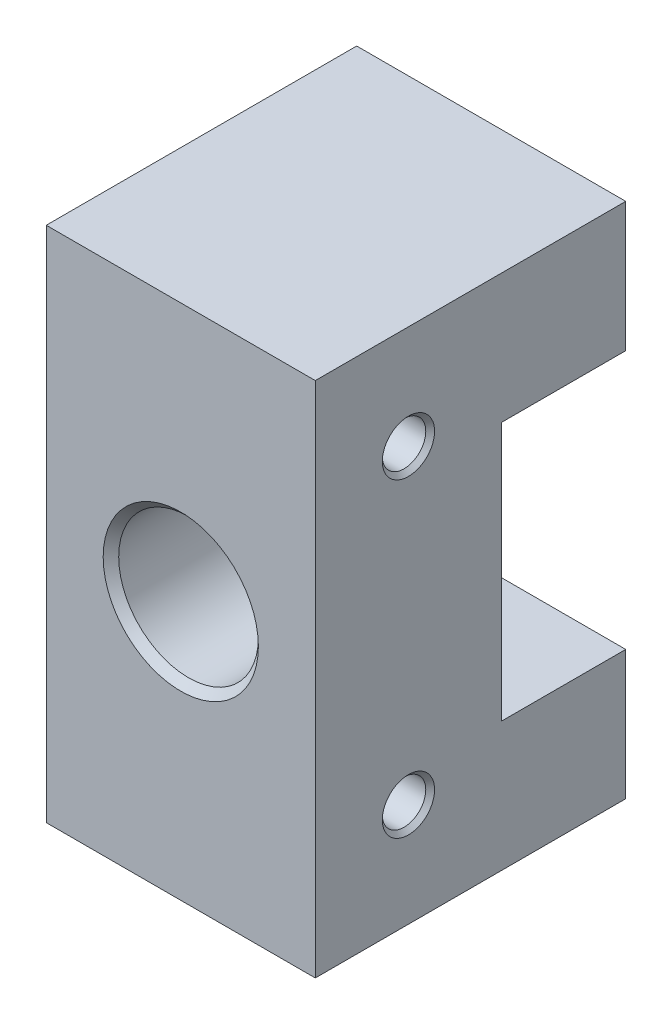
SolidWorks part; units mm, degrees
material "6061 Alloy"
ref_plane "Front Plane" through (0, 0, 0) normal (0, 0, 1) x (1, 0, 0)
ref_plane "Top Plane" through (0, 0, 0) normal (0, 1, 0) x (1, 0, 0)
ref_plane "Right Plane" through (0, 0, 0) normal (1, 0, 0) x (0, 0, -1)
sketch "Sketch1" plane through (0, 0, 0) normal (0, 0, 1) x (1, 0, 0)
  line L1 (-13, 25) -> (13, 25)
  line L2 (-13, 25) -> (-13, -25)
  line L3 (-13, -25) -> (13, -25)
  line L4 (13, 25) -> (13, -25)
  line L5 (-13, 25) -> (13, -25) construction
  line L6 (-13, -25) -> (13, 25) construction
  point P0 (0, 0)
  dimension "D1" = 50
  dimension "D2" = 26
extrude "Boss-Extrude1" add sketch "Sketch1" along normal blind 30
sketch "Sketch2" plane through (0, 0, 0) normal (0, 0, 1) x (1, 0, 0)
  line L0 (-13, 25) -> (-13, -25) construction
  line L1 (13, 12.5) -> (-13, 12.5)
  line L2 (13, 12.5) -> (13, -12.5)
  line L3 (13, -12.5) -> (-13, -12.5)
  line L4 (-13, 12.5) -> (-13, -12.5)
  line L5 (13, 12.5) -> (-13, -12.5) construction
  line L6 (13, -12.5) -> (-13, 12.5) construction
  point P0 (0, 0)
  dimension "D1" = 25
extrude "Cut-Extrude1" cut sketch "Sketch2" along normal blind 12
hole_wizard "M12 Clearance Hole1" positions "Sketch7" profile "Sketch8" hole size "M12" standard "ANSI Metric" end condition up to next
sketch "Sketch7" plane through (0, 0, 12) normal (0, 0, -1) x (-1, 0, 0)
  point P0 (0, 0)
sketch "Sketch8" plane through (0, 0, 12) normal (1, 0, 0) x (0, 1, 0)
  line L0 (0, 0) -> (0, 18)
  line L1 (0, 18) -> (7.5, 18)
  line L2 (6.75, 17.25) -> (6.75, 0.75)
  line L3 (6.75, 0.75) -> (7.5, 0)
  line L5 (7.5, 0) -> (0, 0)
  line L6 (-6.75, 0.75) -> (-7.5, 0) construction
  line L7 (7.5, 18) -> (6.75, 17.25)
  line L8 (-7.5, 18) -> (-6.75, 17.25) construction
  line L11 (0, -6.35) -> (0, 107.95) construction
  dimension "Thru Hole Dia." = 13.5
  dimension "Thru Hole Depth" = 18
  dimension "Near C'Sink Dia." = 15
  dimension "Near C'Sink Angle" = 90
  dimension "Far C'Sink Dia." = 15
  dimension "Far C'Sink Angle" = 90
hole_wizard "M5x0.8 Tapped Hole1" positions "Sketch10" profile "Sketch11" tap size "M5x0.8" standard "ANSI Metric"
sketch "Sketch10" plane through (13, 0, 0) normal (1, 0, 0) x (0, 0, -1)
  line L0 (-21, 15) -> (-21, -15) construction
  line L2 (-30, 0) -> (-12, 0) construction
  line L3 (-30, -25) -> (-30, 25) construction
  line L4 (-12, -12.5) -> (-12, 12.5) construction
  point P0 (-21, 15)
  point P2 (-21, -15)
  point P16 (-21, 0)
  dimension "D1" = 30
sketch "Sketch11" plane through (13, 15, 21) normal (0, 1, 0) x (0, 0, -1)
  line L0 (0, 0) -> (0, 12)
  line L1 (0, 12) -> (2.1, 10.7382)
  line L2 (2.1, 10.7382) -> (2.1, 0.425)
  line L3 (2.1, 0.425) -> (2.525, 0)
  line L5 (2.525, 0) -> (0, 0)
  line L6 (-2.1, 0.425) -> (-2.525, 0) construction
  line L10 (0, 12) -> (-2.1, 10.7382) construction
  line L11 (0, -6.35) -> (0, 107.95) construction
  dimension "Tap Drill Dia." = 4.2
  dimension "Tap Drill Depth" = 12
  dimension "Near C'Sink Dia." = 5.05
  dimension "Near C'Sink Angle" = 90
  dimension "Drill Angle" = 118
cosmetic thread "Hole Thread1"
cosmetic thread "Hole Thread2"
mirror "Mirror1" about plane through (0, 0, 0) normal (1, 0, 0) of "M5x0.8 Tapped Hole1"
cosmetic thread "Hole Thread3"
cosmetic thread "Hole Thread4"
